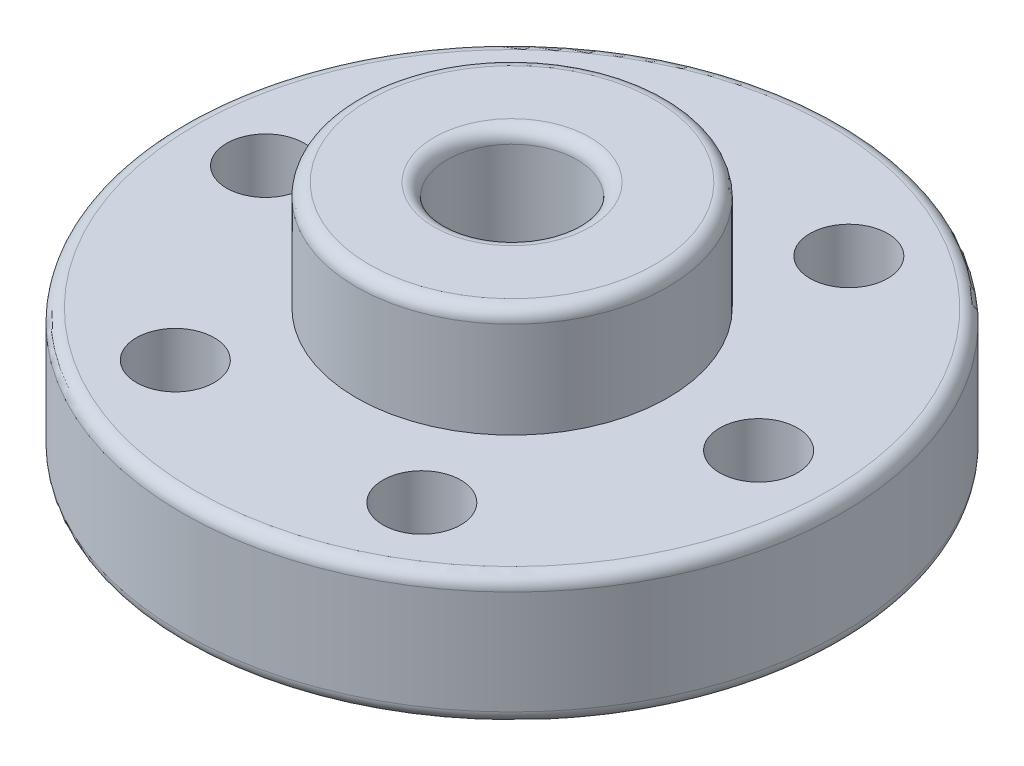
SolidWorks part; units mm, degrees
material "3003 Alloy"
ref_plane "Front Plane" through (0, 0, 0) normal (0, 0, 1) x (1, 0, 0)
ref_plane "Top Plane" through (0, 0, 0) normal (0, 1, 0) x (1, 0, 0)
ref_plane "Right Plane" through (0, 0, 0) normal (1, 0, 0) x (0, 0, -1)
ref_plane "Plane1"
sketch "Sketch1" plane through (0, 0, 0) normal (0, 1, 0) x (-1, 0, 0)
  circle A0 centre (0, 0) radius 12.7
  circle A1 centre (4.75, -8.2272) radius 1.5
  circle A2 centre (9.5, 0) radius 1.5
  circle A3 centre (4.75, 8.2272) radius 1.5
  circle A4 centre (-4.75, 8.2272) radius 1.5
  circle A5 centre (-9.5, 0) radius 1.5
  circle A6 centre (0, 0) radius 2.5
  circle A7 centre (-4.75, -8.2272) radius 1.5
  dimension "D1" = 25.4
  dimension "D2" = 5
  dimension "D3" = 3
  dimension "D4" = 9.5
extrude "Extrusion1" add sketch "Sketch1" along normal blind 5 contours A0 A7 A6 A5 A4 A3 A2 A1
ref_plane "Plane2"
sketch "Sketch2" plane through (0, 5, 0) normal (0, 1, 0) x (1, 0, 0)
  circle A0 centre (0, 0) radius 6
  circle A1 centre (0, 0) radius 2.5
  dimension "D1" = 12
  dimension "D2" = 5
extrude "Extrusion2" add sketch "Sketch2" along normal blind 4.2 contours A0 A1
fillet "Fillet1" radius 0.5 5 edges at (0, 0, 2.5) (0, 0, 12.7) (0, 9.2, 2.5) (0, 5, 12.7) (0, 9.2, 6)
